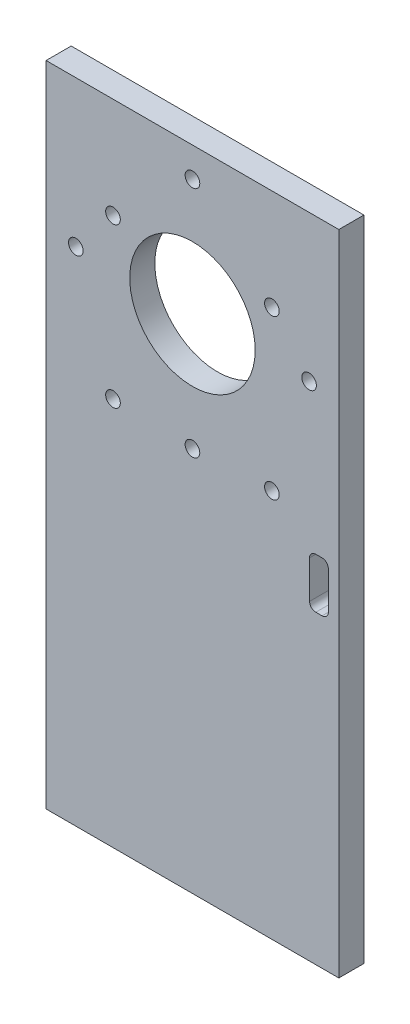
SolidWorks part; units mm, degrees
ref_plane "Front Plane" through (0, 0, 0) normal (0, 0, 1) x (1, 0, 0)
ref_plane "Top Plane" through (0, 0, 0) normal (0, 1, 0) x (1, 0, 0)
ref_plane "Right Plane" through (0, 0, 0) normal (1, 0, 0) x (0, 0, -1)
sketch "Sketch1" plane through (0, 0, 0) normal (0, 0, 1) x (1, 0, 0)
  line L1 (-35, 77.5) -> (35, 77.5)
  line L2 (-35, 77.5) -> (-35, -77.5)
  line L3 (-35, -77.5) -> (35, -77.5)
  line L4 (35, 77.5) -> (35, -77.5)
  line L5 (-35, 77.5) -> (35, -77.5) construction
  line L6 (-35, -77.5) -> (35, 77.5) construction
  point P0 (0, 0)
  dimension "D1" = 70
  dimension "D2" = 155
extrude "Boss-Extrude1" add sketch "Sketch1" along normal blind 6
sketch "Sketch3" plane through (0, 0, 6) normal (0, 0, 1) x (1, 0, 0)
  line L0 (0, 0) -> (0, 77.5) construction
  line L1 (35, 77.5) -> (-35, 77.5) construction
  circle A0 centre (0, 42.5) radius 15
  dimension "D2" = 30
  dimension "D1" = 35
extrude "Cut-Extrude1" cut sketch "Sketch3" against normal through all
sketch "Sketch4" plane through (0, 0, 0) normal (0, 0, -1) x (-1, 0, 0)
  circle A0 centre (-19, 53.4) radius 1.75
  circle A1 centre (19, 53.4) radius 1.75
  circle A2 centre (-19, 15.4) radius 1.75
  circle A3 centre (19, 15.4) radius 1.75
  dimension "D1" = 3.5
extrude "Cut-Extrude2" cut sketch "Sketch4" against normal through all
sketch "Sketch5" plane through (0, 0, 6) normal (0, 0, 1) x (1, 0, 0)
  line L0 (35, -77.5) -> (35, 77.5) construction
  line L1 (30.25, 7.5) -> (30.25, -4.5) construction
  line L2 (29.5, 7.5) -> (31, 7.5)
  line L3 (32.5, 6) -> (32.5, -3)
  line L4 (31, -4.5) -> (29.5, -4.5)
  line L5 (28, -3) -> (28, 6)
  line L6 (26.5, 10) -> (34, 10) construction
  line L7 (26.5, 10) -> (26.5, -7) construction
  line L8 (26.5, -7) -> (34, -7) construction
  line L9 (34, 10) -> (34, -7) construction
  line L10 (26.5, 10) -> (34, -7) construction
  line L11 (26.5, -7) -> (34, 10) construction
  line L12 (35, 77.5) -> (-35, 77.5) construction
  arc A0 (29.5, 7.5) -> (28, 6) centre (29.5, 6) ccw
  arc A1 (29.5, -4.5) -> (28, -3) centre (29.5, -3) cw
  arc A2 (32.5, -3) -> (31, -4.5) centre (31, -3) cw
  arc A3 (31, 7.5) -> (32.5, 6) centre (31, 6) cw
  point P7 (28, -4.5)
  point P14 (32.5, -4.5)
  point P17 (30.25, 1.5)
  point P18 (30.25, 1.5)
  dimension "D1" = 1.5
  dimension "D2" = 17
  dimension "D3" = 12
  dimension "D4" = 4.5
  dimension "D5" = 7.5
  dimension "D6" = 1
  dimension "D7" = 70
extrude "Cut-Extrude3" cut sketch "Sketch5" against normal through all
sketch "Sketch8" plane through (0, 0, 6) normal (0, 0, 1) x (1, 0, 0)
  circle A0 centre (-27.888, 42.5) radius 1.75
  circle A1 centre (0, 14.612) radius 1.75
  circle A2 centre (27.888, 42.5) radius 1.75
  circle A3 centre (0, 70.388) radius 1.75
  dimension "D1" = 3.5
extrude "Cut-Extrude6" cut sketch "Sketch8" against normal through all
